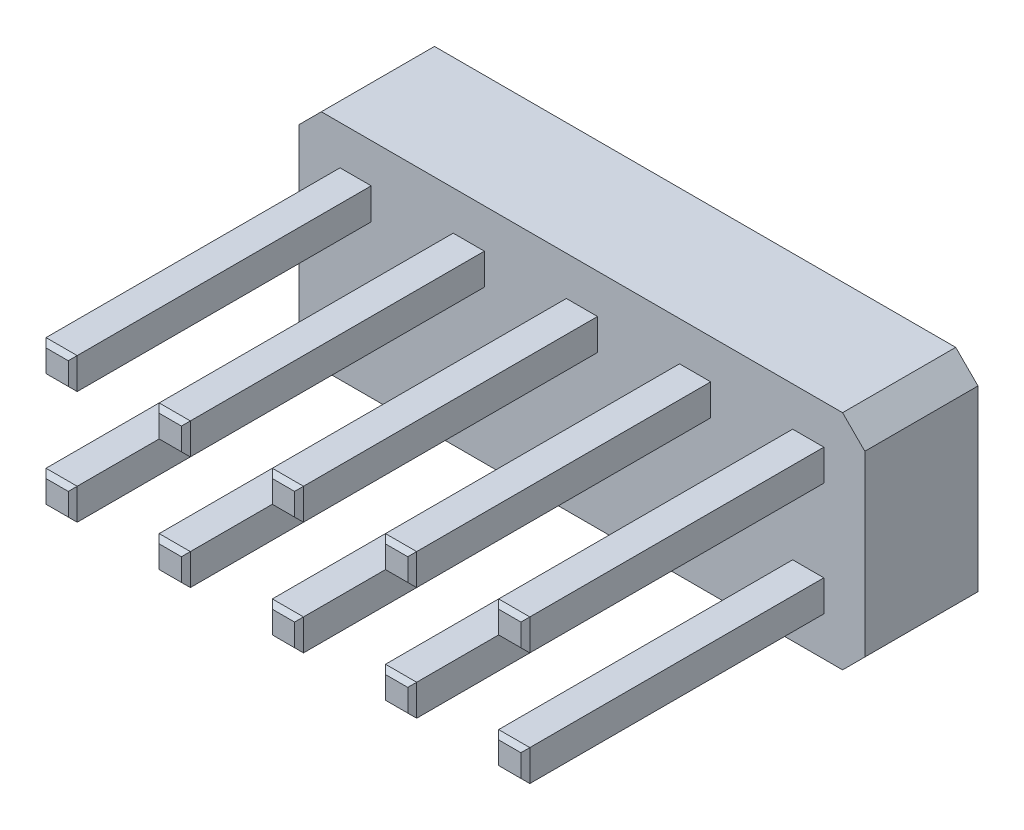
SolidWorks part; units mm, degrees
ref_plane "Front Plane" through (0, 0, 0) normal (0, 0, 1) x (1, 0, 0)
ref_plane "Top Plane" through (0, 0, 0) normal (0, 1, 0) x (1, 0, 0)
ref_plane "Right Plane" through (0, 0, 0) normal (1, 0, 0) x (0, 0, -1)
sketch "Sketch1" plane through (0, 0, 0) normal (0, 0, 1) x (1, 0, 0)
  line L1 (-6.35, 2.5) -> (6.35, 2.5)
  line L2 (-6.35, 2.5) -> (-6.35, -2.5)
  line L3 (-6.35, -2.5) -> (6.35, -2.5)
  line L4 (6.35, 2.5) -> (6.35, -2.5)
  line L5 (-6.35, 2.5) -> (6.35, -2.5) construction
  line L6 (-6.35, -2.5) -> (6.35, 2.5) construction
  point P0 (0, 0)
  dimension "D1" = 5
  dimension "D2" = 12.7
extrude "Boss-Extrude1" add sketch "Sketch1" along normal blind 2.54
sketch "Sketch2" plane through (0, 0, 2.54) normal (0, 0, 1) x (1, 0, 0)
  line L0 (-2.89, 1.62) -> (-2.19, 1.62)
  line L1 (-5.43, 1.62) -> (-4.73, 1.62)
  line L2 (-5.43, 1.62) -> (-5.43, 0.92)
  line L3 (-5.43, 0.92) -> (-4.73, 0.92)
  line L4 (-4.73, 1.62) -> (-4.73, 0.92)
  line L5 (-2.19, 1.62) -> (-2.19, 0.92)
  line L6 (-2.89, 0.92) -> (-2.19, 0.92)
  line L7 (-2.89, 1.62) -> (-2.89, 0.92)
  line L8 (-0.35, 1.62) -> (0.35, 1.62)
  line L9 (0.35, 1.62) -> (0.35, 0.92)
  line L10 (-0.35, 0.92) -> (0.35, 0.92)
  line L11 (-0.35, 1.62) -> (-0.35, 0.92)
  line L12 (2.19, 1.62) -> (2.89, 1.62)
  line L13 (2.89, 1.62) -> (2.89, 0.92)
  line L14 (2.19, 0.92) -> (2.89, 0.92)
  line L15 (2.19, 1.62) -> (2.19, 0.92)
  line L16 (4.73, 1.62) -> (5.43, 1.62)
  line L17 (5.43, 1.62) -> (5.43, 0.92)
  line L18 (4.73, 0.92) -> (5.43, 0.92)
  line L19 (4.73, 1.62) -> (4.73, 0.92)
  line L20 (-2.89, -0.92) -> (-2.19, -0.92)
  line L21 (-2.19, -0.92) -> (-2.19, -1.62)
  line L22 (-2.89, -1.62) -> (-2.19, -1.62)
  line L23 (-2.89, -0.92) -> (-2.89, -1.62)
  line L24 (-0.35, -0.92) -> (0.35, -0.92)
  line L25 (0.35, -0.92) -> (0.35, -1.62)
  line L26 (-0.35, -1.62) -> (0.35, -1.62)
  line L27 (-0.35, -0.92) -> (-0.35, -1.62)
  line L28 (2.19, -0.92) -> (2.89, -0.92)
  line L29 (2.89, -0.92) -> (2.89, -1.62)
  line L30 (2.19, -1.62) -> (2.89, -1.62)
  line L31 (2.19, -0.92) -> (2.19, -1.62)
  line L32 (4.73, -0.92) -> (5.43, -0.92)
  line L33 (5.43, -0.92) -> (5.43, -1.62)
  line L34 (4.73, -1.62) -> (5.43, -1.62)
  line L35 (4.73, -0.92) -> (4.73, -1.62)
  line L36 (-5.43, -0.92) -> (-4.73, -0.92)
  line L37 (-4.73, -0.92) -> (-4.73, -1.62)
  line L38 (-5.43, -1.62) -> (-4.73, -1.62)
  line L39 (-5.43, -0.92) -> (-5.43, -1.62)
  line L40 (-5.43, 1.62) -> (-2.89, 1.62) construction
  line L41 (-5.43, 1.62) -> (-5.43, -0.92) construction
  line L42 (0, 0) -> (0, 0.92) construction
  line L43 (0, 0) -> (0, -0.92) construction
  dimension "D1" = 0.7
  dimension "D4" = 2.54
  dimension "D5" = 2.54
  dimension "D2" = 5
  dimension "D3" = 2
extrude "Boss-Extrude2" add sketch "Sketch2" along normal blind 6.7
chamfer "Chamfer1" distance 0.5 angle 45 4 edges at (6.35, 2.5, 1.27) (6.35, -2.5, 1.27) (-6.35, 2.5, 1.27) (-6.35, -2.5, 1.27)
chamfer "Chamfer2" distance 0.1 angle 45 40 edges at (-5.08, 1.62, 9.24) (-4.73, 1.27, 9.24) (-5.08, 0.92, 9.24) (-5.43, 1.27, 9.24) (-5.43, -1.27, 9.24) (-5.08, -0.92, 9.24) (-4.73, -1.27, 9.24) (-5.08, -1.62, 9.24) (-2.54, -0.92, 9.24) (-2.19, -1.27, 9.24) (-2.54, -1.62, 9.24) (-2.89, -1.27, 9.24) (0, -0.92, 9.24) (0.35, -1.27, 9.24) (0, -1.62, 9.24) (-0.35, -1.27, 9.24) (2.54, -0.92, 9.24) (2.89, -1.27, 9.24) (2.54, -1.62, 9.24) (2.19, -1.27, 9.24) (5.08, -0.92, 9.24) (5.43, -1.27, 9.24) (5.08, -1.62, 9.24) (4.73, -1.27, 9.24) (5.08, 1.62, 9.24) (5.43, 1.27, 9.24) (5.08, 0.92, 9.24) (4.73, 1.27, 9.24) (2.54, 1.62, 9.24) (2.89, 1.27, 9.24) (2.54, 0.92, 9.24) (2.19, 1.27, 9.24) (0, 1.62, 9.24) (0.35, 1.27, 9.24) (0, 0.92, 9.24) (-0.35, 1.27, 9.24) (-2.54, 1.62, 9.24) (-2.19, 1.27, 9.24) (-2.54, 0.92, 9.24) (-2.89, 1.27, 9.24)
